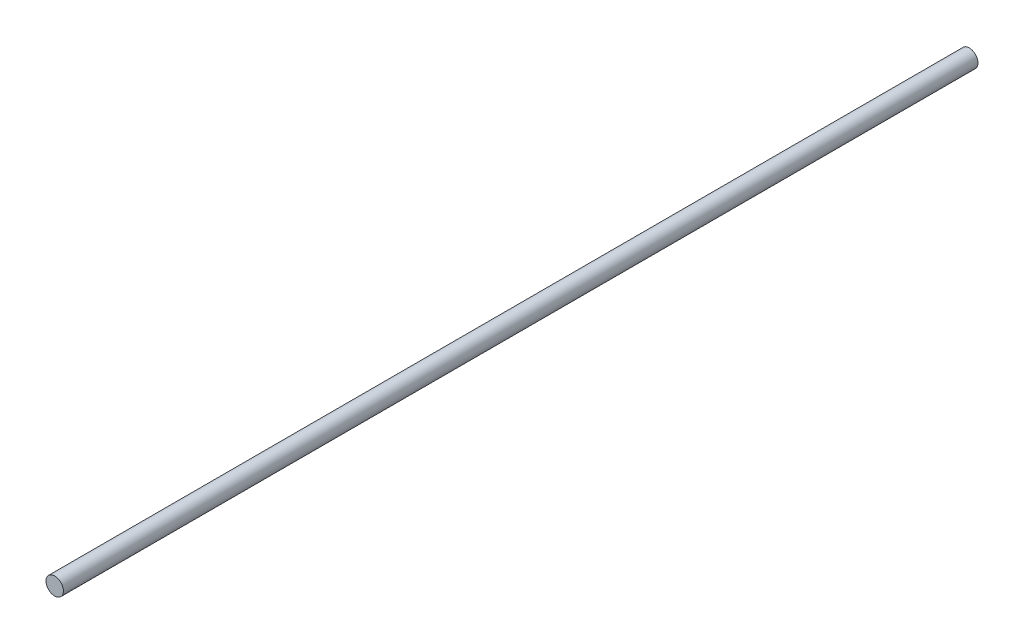
SolidWorks part; units mm, degrees
ref_plane "Front" through (0, 0, 0) normal (0, 0, 1) x (1, 0, 0)
ref_plane "Top" through (0, 0, 0) normal (0, 1, 0) x (1, 0, 0)
ref_plane "Right" through (0, 0, 0) normal (1, 0, 0) x (0, 0, -1)
sketch "Sketch1" plane through (0, 0, 0) normal (0, 0, 1) x (1, 0, 0)
  circle A0 centre (0, 0) radius 4
  dimension "D1" = 8
extrude "Boss-Extrude1" add sketch "Sketch1" along normal mid plane 420
